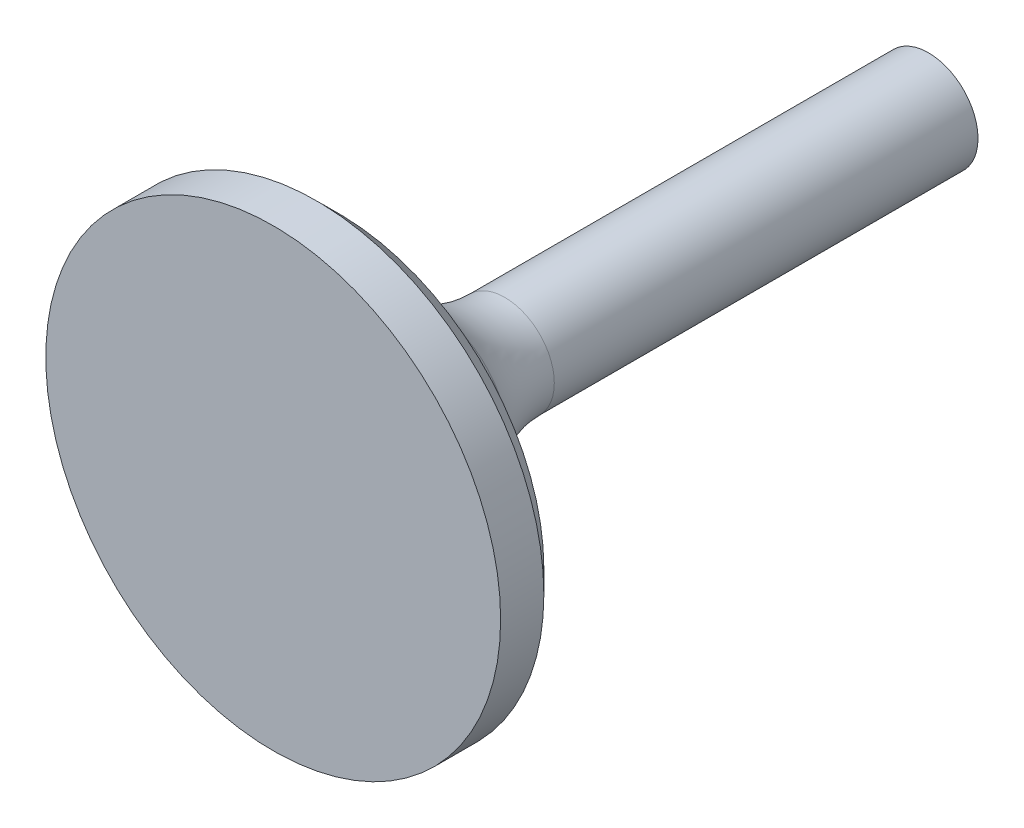
SolidWorks part; units mm, degrees
ref_plane "Front Plane" through (0, 0, 0) normal (0, 0, 1) x (1, 0, 0)
ref_plane "Top Plane" through (0, 0, 0) normal (0, 1, 0) x (1, 0, 0)
ref_plane "Right Plane" through (0, 0, 0) normal (1, 0, 0) x (0, 0, -1)
sketch "Sketch1" plane through (0, 0, 0) normal (0, 1, 0) x (1, 0, 0)
  line L0 (0, 17.0482) -> (0, -23.7761) construction
  line L1 (0, -23.7761) -> (15.4781, -23.7761)
  line L4 (3.3655, -8.0117) -> (3.3655, 20.8232)
  line L5 (0, -23.7761) -> (0, 20.8232)
  line L6 (0, 20.8232) -> (3.3655, 20.8232)
  line L8 (15.4781, -20.8353) -> (13.9303, -19.2875)
  line L9 (15.4781, -23.7761) -> (15.4781, -20.8353)
  arc A1 (3.3655, -8.0117) -> (5.1654, -12.9706) centre (11.0966, -8.0117) ccw
  spline S0 degree 3 poles (13.9303, -19.2875) (10.3196, -18.1513) (7.5547, -15.8284) (5.1654, -12.9706) knots 0 0 0 0 0.79734 0.79734 0.79734 0.79734
  dimension "D5" = 2.9408
  dimension "D6" = 7.7311
  dimension "D1" = 15.4781
  dimension "D2" = 13.9303
  dimension "D3" = 45
  dimension "D4" = 6.731
revolve "Revolve1" add sketch "Sketch1" angle 360 about L5
